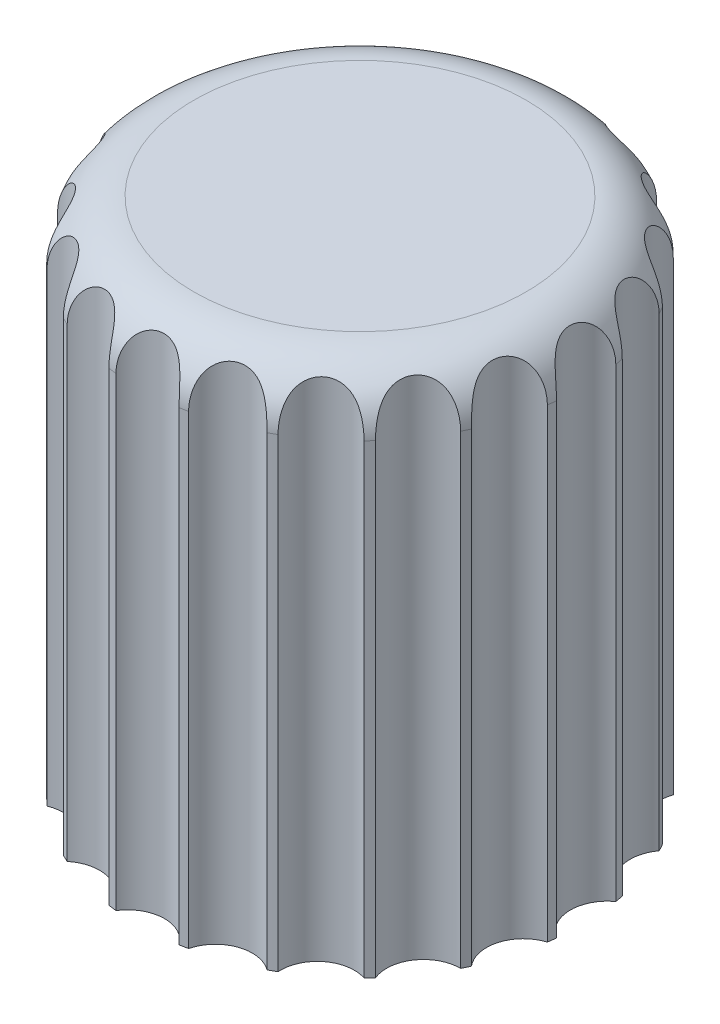
SolidWorks part; units mm, degrees
ref_plane "Front Plane" through (0, 0, 0) normal (0, 0, 1) x (1, 0, 0)
ref_plane "Top Plane" through (0, 0, 0) normal (0, 1, 0) x (1, 0, 0)
ref_plane "Right Plane" through (0, 0, 0) normal (1, 0, 0) x (0, 0, -1)
sketch "Sketch1" plane through (0, 0, 0) normal (0, 1, 0) x (1, 0, 0)
  line L0 (0, 6) -> (0, 0) construction
  line L1 (0, 0) -> (0, 3) construction
  line L2 (0, 3) -> (-0.4, 3) construction
  line L3 (0, 3) -> (0.4, 3) construction
  line L5 (-0.4, 5.9867) -> (0.4, 5.9867)
  line L6 (-0.4, 5.9867) -> (-0.4, -5.9867)
  line L7 (-0.4, -5.9867) -> (0.4, -5.9867)
  line L8 (0.4, 5.9867) -> (0.4, -5.9867)
  circle A0 centre (0, 0) radius 6
  circle A1 centre (0, 0) radius 5.25
  dimension "D1" = 12
  dimension "D4" = 10.5
  dimension "D2" = 0.4
  dimension "D3" = 0.4
extrude "Boss-Extrude1" add sketch "Sketch1" along normal blind 12.1 contours L6 L7 L8 L5 | A1 | A0
sketch "Sketch4" plane through (0, 12.1, 0) normal (0, 1, 0) x (1, 0, 0)
  circle A0 centre (0, 0) radius 6
extrude "Boss-Extrude2" add sketch "Sketch4" along normal blind 2
fillet "Fillet1" radius 1.5 1 edges at (0, 14.1, 6)
sketch "Sketch7" plane through (0, 14.1, 0) normal (0, 1, 0) x (1, 0, 0)
  circle A0 centre (0, 0) radius 6.5
  circle A1 centre (-6.2415, 1.8148) radius 1
  circle A2 centre (-5.3752, 3.6547) radius 1
  circle A3 centre (-3.9828, 5.1369) radius 1
  circle A4 centre (-2.2005, 6.1162) radius 1
  circle A5 centre (-0.2028, 6.4968) radius 1
  circle A6 centre (1.8148, 6.2415) radius 1
  circle A7 centre (3.6547, 5.3752) radius 1
  circle A8 centre (5.1369, 3.9828) radius 1
  circle A9 centre (6.1162, 2.2005) radius 1
  circle A10 centre (6.4968, 0.2028) radius 1
  circle A11 centre (6.2415, -1.8148) radius 1
  circle A12 centre (5.3752, -3.6547) radius 1
  circle A13 centre (3.9828, -5.1369) radius 1
  circle A14 centre (2.2005, -6.1162) radius 1
  circle A15 centre (0.2028, -6.4968) radius 1
  circle A16 centre (-1.8148, -6.2415) radius 1
  circle A17 centre (-3.6547, -5.3752) radius 1
  circle A18 centre (-5.1369, -3.9828) radius 1
  circle A19 centre (-6.1162, -2.2005) radius 1
  circle A20 centre (-6.4968, -0.2028) radius 1
  point P45 (0, 0)
  dimension "D1" = 13
  dimension "D2" = 2
  dimension "D3" = 20
extrude "Cut-Extrude6" cut sketch "Sketch7" against normal blind 25 contours A0 A1 | A0 A2 | A0 A3 | A0 A4 | A0 A5 | A0 A6 | A0 A7 | A0 A8 | A0 A9 | A0 A10 | A0 A11 | A0 A12 | A0 A13 | A0 A14 | A0 A15 | A0 A16 | A0 A17 | A0 A18 | A0 A19 | A0 A20
